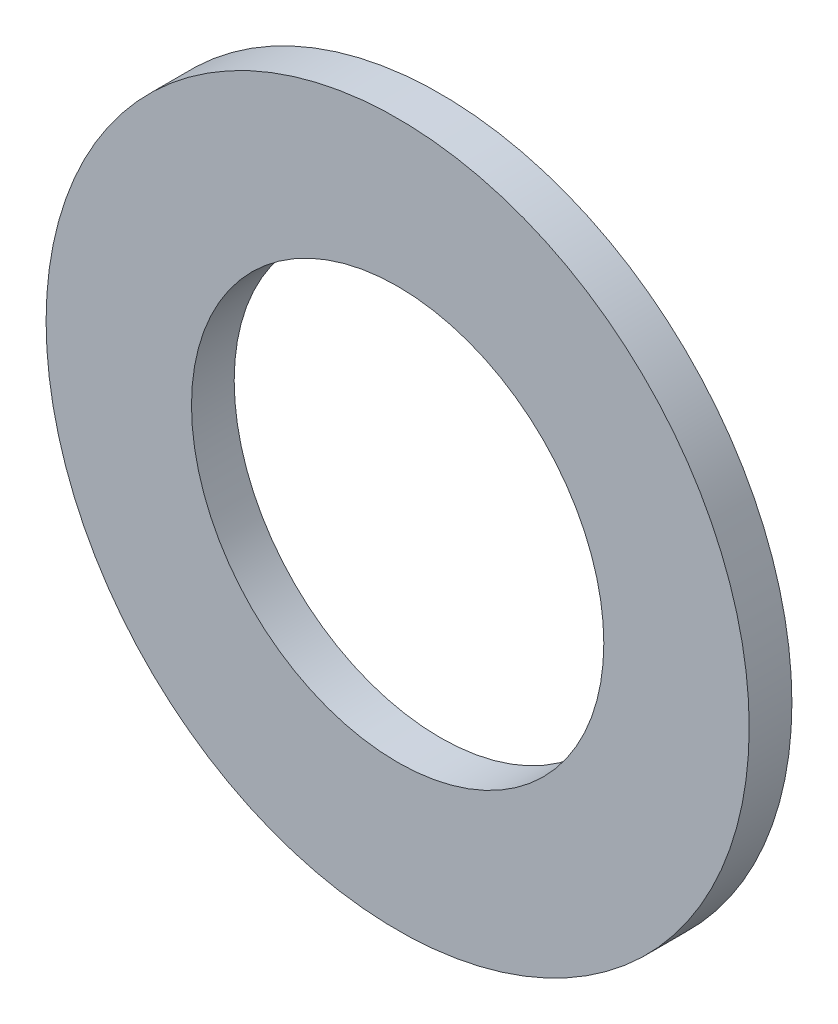
SolidWorks part; units mm, degrees
ref_plane "Front Plane" through (0, 0, 0) normal (0, 0, 1) x (1, 0, 0)
ref_plane "Top Plane" through (0, 0, 0) normal (0, 1, 0) x (1, 0, 0)
ref_plane "Right Plane" through (0, 0, 0) normal (1, 0, 0) x (0, 0, -1)
sketch "Sketch1" plane through (0, 0, 0) normal (0, 0, 1) x (1, 0, 0)
  circle A0 centre (0, 0) radius 11.9366
  circle A1 centre (0, 0) radius 7
extrude "Boss-Extrude1" add sketch "Sketch1" along normal blind 1.45
